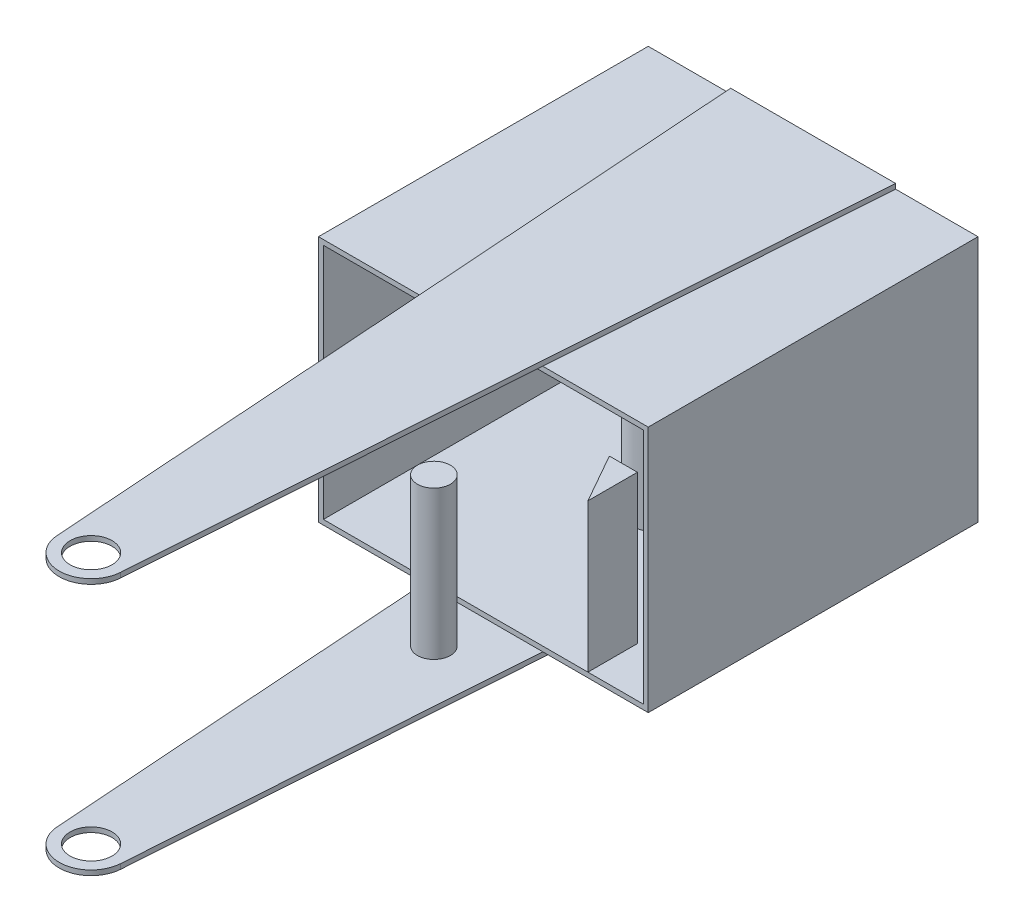
SolidWorks part; units mm, degrees
ref_plane "Alzado" through (0, 0, 0) normal (0, 0, 1) x (1, 0, 0)
ref_plane "Planta" through (0, 0, 0) normal (0, 1, 0) x (1, 0, 0)
ref_plane "Vista lateral" through (0, 0, 0) normal (1, 0, 0) x (0, 0, -1)
sketch "Croquis1" plane through (0, 0, 0) normal (0, 0, 1) x (1, 0, 0)
  line L1 (0, 0) -> (200, 0)
  line L2 (0, 0) -> (0, 150)
  line L3 (0, 150) -> (200, 150)
  line L4 (200, 0) -> (200, 150)
  dimension "D1" = 200
  dimension "D2" = 150
extrude "Saliente-Extruir1" add sketch "Croquis1" along normal blind 200
shell "Vaciado1" thickness 3
sketch "Croquis2" plane through (0, 150, 0) normal (0, 1, 0) x (1, 0, 0)
  line L0 (119.2838, 439.2627) -> (150, 0) construction
  line L1 (150, 0) -> (50, 0)
  line L2 (100, 0) -> (100, 81.8712) construction
  line L3 (80.7162, 439.2627) -> (50, 0) construction
  line L4 (0, -200) -> (200, -200) construction
  line L5 (80.7162, -439.2627) -> (50, 0)
  line L6 (200, 0) -> (0, 0) construction
  line L7 (119.2838, -439.2627) -> (150, 0)
  arc A0 (119.2838, 439.2627) -> (80.7162, 439.2627) centre (100, 437.9142) ccw construction
  circle A1 centre (100, 437.9142) radius 12.7 construction
  circle A2 centre (100, -437.9142) radius 12.7
  arc A3 (119.2838, -439.2627) -> (80.7162, -439.2627) centre (100, -437.9142) cw
  point P10 (151.0425, 0)
  point P15 (100, 0)
  dimension "D3" = 25.4
  dimension "D1" = 50
  dimension "D2" = 86
  dimension "D4" = 437.9142
extrude "Saliente-Extruir2" add sketch "Croquis2" along normal blind 3
ref_plane "Plano1" through (0, 75, 0) normal (0, -1, 0) x (-1, 0, 0)
mirror "Simetría1" about plane through (0, 75, 0) normal (0, -1, 0) of "Saliente-Extruir2"
sketch "Croquis3" plane through (0, 3, 0) normal (0, 1, 0) x (1, 0, 0)
  line L1 (150, 0) -> (50, 0) construction
  circle A0 centre (100, -95) radius 85 construction
  circle A1 centre (100, -230) radius 50 construction
  point P4 (163.84, -213.9515)
  point P5 (100, 0)
  point P8 (0, 0)
  point P9 (0, 0)
  point P10 (0, 0)
  dimension "D1" = 170
  dimension "D3" = 100
  dimension "D2" = 95
sketch "Croquis4" plane through (0, 3, 0) normal (0, 1, 0) x (1, 0, 0)
  circle A0 centre (100, -95) radius 15
  dimension "D1" = 30
extrude "Saliente-Extruir3" add sketch "Croquis4" along normal blind 90
sketch "Croquis6" plane through (0, 0, 0) normal (0, 1, 0) x (1, 0, 0)
  circle A0 centre (100, -230) radius 10
  dimension "D1" = 20
extrude "Saliente-Extruir4" add sketch "Croquis6" along normal blind 90
sketch "Croquis7" plane through (0, 3, 0) normal (0, 1, 0) x (1, 0, 0)
  line L0 (146.4296, -170) -> (163.4296, -170)
  line L1 (163.4296, -170) -> (163.4296, -200)
  line L2 (200, -200) -> (136.0146, -200) construction
  line L3 (163.4296, -200) -> (146.4296, -170)
  line L4 (200, -200) -> (200, 0) construction
  dimension "D1" = 30
  dimension "D2" = 17
  dimension "D3" = 36.5704
extrude "Saliente-Extruir5" add sketch "Croquis7" along normal blind 90
